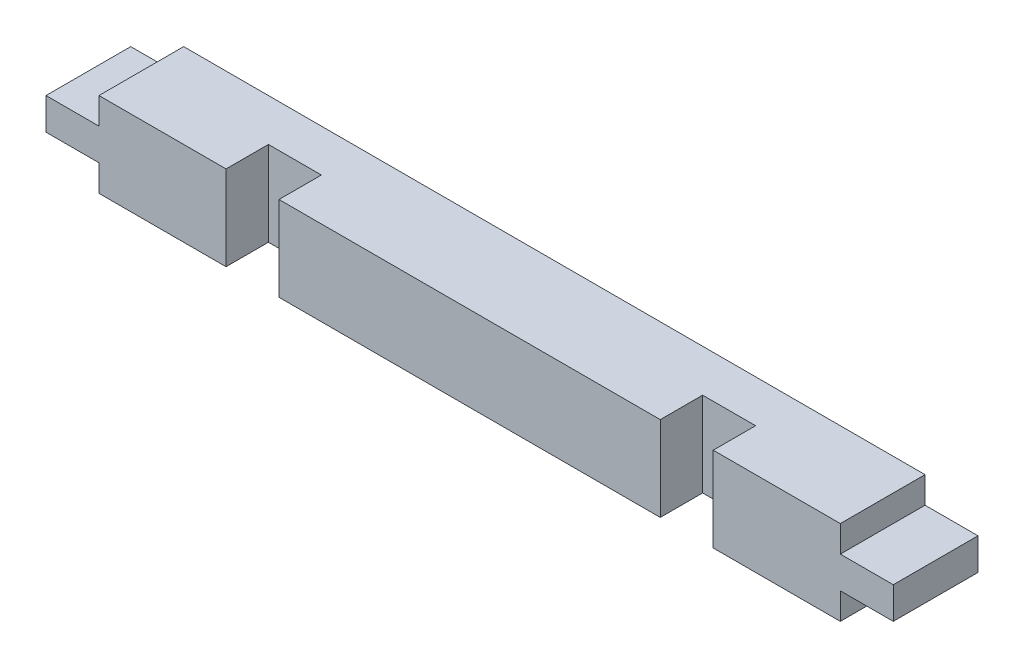
SolidWorks part; units mm, degrees
ref_plane "Front Plane" through (0, 0, 0) normal (0, 0, 1) x (1, 0, 0)
ref_plane "Top Plane" through (0, 0, 0) normal (0, 1, 0) x (1, 0, 0)
ref_plane "Right Plane" through (0, 0, 0) normal (1, 0, 0) x (0, 0, -1)
sketch "Sketch1" plane through (0, 0, 0) normal (0, 0, 1) x (1, 0, 0)
  line L0 (0, 0) -> (0, 3)
  line L1 (0, 3) -> (5, 3)
  line L2 (5, 3) -> (5, 5.5)
  line L3 (5, 5.5) -> (75, 5.5)
  line L4 (75, 5.5) -> (75, 3)
  line L5 (75, 3) -> (80, 3)
  line L6 (80, 3) -> (80, 0)
  line L7 (80, 0) -> (75, 0)
  line L8 (75, 0) -> (75, -2.5)
  line L9 (75, -2.5) -> (5, -2.5)
  line L10 (5, -2.5) -> (5, 0)
  line L11 (5, 0) -> (0, 0)
  dimension "D1" = 80
  dimension "D2" = 70
  dimension "D3" = 3
  dimension "D4" = 8
extrude "Boss-Extrude1" add sketch "Sketch1" along normal blind 8
sketch "Sketch2" plane through (0, 0, 8) normal (0, 0, 1) x (1, 0, 0)
  line L0 (5, -2.5) -> (75, -2.5) construction
  line L1 (17, -2.5) -> (22, -2.5)
  line L2 (17, -2.5) -> (17, 5.5)
  line L3 (17, 5.5) -> (22, 5.5)
  line L4 (22, -2.5) -> (22, 5.5)
  line L5 (5, 0) -> (5, -2.5) construction
  line L6 (58, -2.5) -> (63, -2.5)
  line L7 (58, -2.5) -> (58, 5.5)
  line L8 (58, 5.5) -> (63, 5.5)
  line L9 (63, -2.5) -> (63, 5.5)
  line L10 (75, -2.5) -> (75, 0) construction
  line L11 (75, 5.5) -> (5, 5.5) construction
  dimension "D1" = 12
  dimension "D2" = 5
  dimension "D3" = 12
extrude "Cut-Extrude1" cut sketch "Sketch2" against normal blind 4
